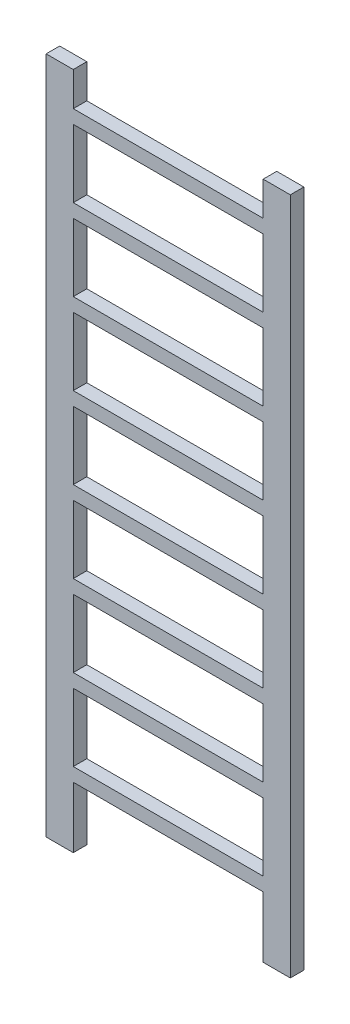
SolidWorks part; units mm, degrees
ref_plane "前视基准面" through (0, 0, 0) normal (0, 0, 1) x (1, 0, 0)
ref_plane "上视基准面" through (0, 0, 0) normal (0, 1, 0) x (1, 0, 0)
ref_plane "右视基准面" through (0, 0, 0) normal (1, 0, 0) x (0, 0, -1)
other "Configuration Table"
sketch "草图1" plane through (0, 0, 0) normal (0, 0, 1) x (1, 0, 0)
  line L1 (-450, -1250) -> (-350, -1250)
  line L2 (-450, -1250) -> (-450, 1250)
  line L3 (-450, 1250) -> (-350, 1250)
  line L4 (-350, -1250) -> (-350, 1250)
  line L5 (-450, -1250) -> (-350, 1250) construction
  line L6 (-450, 1250) -> (-350, -1250) construction
  point P0 (-400, 0)
extrude "凸台-拉伸1" add sketch "草图1" along normal blind 50
sketch "草图2" plane through (0, 0, 0) normal (0, 0, 1) x (1, 0, 0)
  line L1 (350, -1250) -> (450, -1250)
  line L2 (350, -1250) -> (350, 1250)
  line L3 (350, 1250) -> (450, 1250)
  line L4 (450, -1250) -> (450, 1250)
  line L5 (350, -1250) -> (450, 1250) construction
  line L6 (350, 1250) -> (450, -1250) construction
  point P0 (400, 0)
extrude "凸台-拉伸2" add sketch "草图2" along normal blind 50
sketch "草图3" plane through (0, 0, 0) normal (0, 0, 1) x (1, 0, 0)
  line L1 (-400, 1075) -> (400, 1075)
  line L2 (-400, 1075) -> (-400, 1125)
  line L3 (-400, 1125) -> (400, 1125)
  line L4 (400, 1075) -> (400, 1125)
  line L5 (-400, 1075) -> (400, 1125) construction
  line L6 (-400, 1125) -> (400, 1075) construction
  point P0 (0, 1100)
extrude "凸台-拉伸3" add sketch "草图3" along normal blind 50
sketch "草图4" plane through (0, 0, 0) normal (0, 0, 1) x (1, 0, 0)
  line L1 (-400, 775) -> (400, 775)
  line L2 (-400, 775) -> (-400, 825)
  line L3 (-400, 825) -> (400, 825)
  line L4 (400, 775) -> (400, 825)
  line L5 (-400, 775) -> (400, 825) construction
  line L6 (-400, 825) -> (400, 775) construction
  point P0 (0, 800)
extrude "凸台-拉伸4" add sketch "草图4" along normal blind 50
sketch "草图5" plane through (0, 0, 0) normal (0, 0, 1) x (1, 0, 0)
  line L1 (-400, 475) -> (400, 475)
  line L2 (-400, 475) -> (-400, 525)
  line L3 (-400, 525) -> (400, 525)
  line L4 (400, 475) -> (400, 525)
  line L5 (-400, 475) -> (400, 525) construction
  line L6 (-400, 525) -> (400, 475) construction
  point P0 (0, 500)
extrude "凸台-拉伸5" add sketch "草图5" along normal blind 50
sketch "草图6" plane through (0, 0, 0) normal (0, 0, 1) x (1, 0, 0)
  line L1 (-400, 175) -> (400, 175)
  line L2 (-400, 175) -> (-400, 225)
  line L3 (-400, 225) -> (400, 225)
  line L4 (400, 175) -> (400, 225)
  line L5 (-400, 175) -> (400, 225) construction
  line L6 (-400, 225) -> (400, 175) construction
  point P0 (0, 200)
extrude "凸台-拉伸6" add sketch "草图6" along normal blind 50
sketch "草图7" plane through (0, 0, 0) normal (0, 0, 1) x (1, 0, 0)
  line L1 (-400, -125) -> (400, -125)
  line L2 (-400, -125) -> (-400, -75)
  line L3 (-400, -75) -> (400, -75)
  line L4 (400, -125) -> (400, -75)
  line L5 (-400, -125) -> (400, -75) construction
  line L6 (-400, -75) -> (400, -125) construction
  point P0 (0, -100)
extrude "凸台-拉伸7" add sketch "草图7" along normal blind 50
sketch "草图8" plane through (0, 0, 0) normal (0, 0, 1) x (1, 0, 0)
  line L1 (-400, -425) -> (400, -425)
  line L2 (-400, -425) -> (-400, -375)
  line L3 (-400, -375) -> (400, -375)
  line L4 (400, -425) -> (400, -375)
  line L5 (-400, -425) -> (400, -375) construction
  line L6 (-400, -375) -> (400, -425) construction
  point P0 (0, -400)
extrude "凸台-拉伸8" add sketch "草图8" along normal blind 50
sketch "草图9" plane through (0, 0, 0) normal (0, 0, 1) x (1, 0, 0)
  line L1 (-400, -725) -> (400, -725)
  line L2 (-400, -725) -> (-400, -675)
  line L3 (-400, -675) -> (400, -675)
  line L4 (400, -725) -> (400, -675)
  line L5 (-400, -725) -> (400, -675) construction
  line L6 (-400, -675) -> (400, -725) construction
  point P0 (0, -700)
extrude "凸台-拉伸9" add sketch "草图9" along normal blind 50
sketch "草图10" plane through (0, 0, 0) normal (0, 0, 1) x (1, 0, 0)
  line L1 (-400, -1025) -> (400, -1025)
  line L2 (-400, -1025) -> (-400, -975)
  line L3 (-400, -975) -> (400, -975)
  line L4 (400, -1025) -> (400, -975)
  line L5 (-400, -1025) -> (400, -975) construction
  line L6 (-400, -975) -> (400, -1025) construction
  point P0 (0, -1000)
extrude "凸台-拉伸10" add sketch "草图10" along normal blind 50
